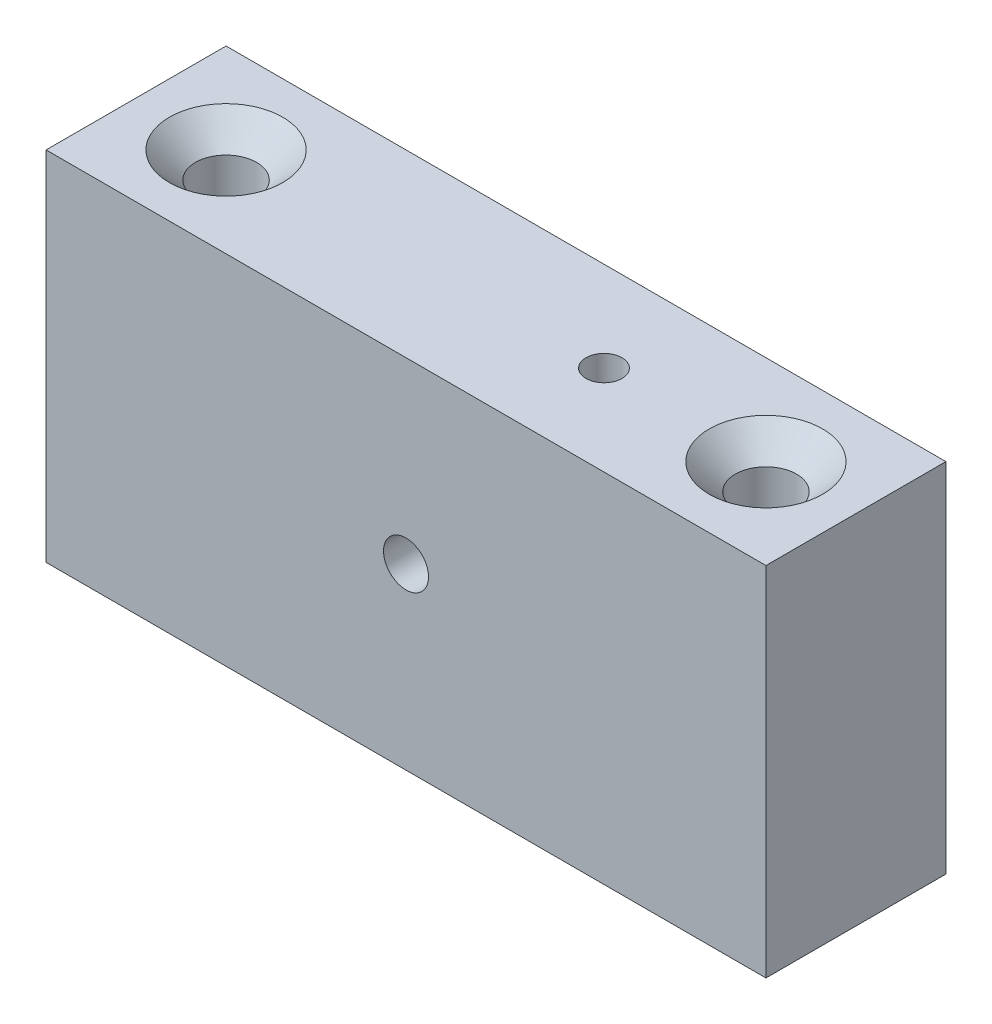
SolidWorks part; units mm, degrees
material "Copper"
ref_plane "Front Plane" through (0, 0, 0) normal (0, 0, 1) x (1, 0, 0)
ref_plane "Top Plane" through (0, 0, 0) normal (0, 1, 0) x (1, 0, 0)
ref_plane "Right Plane" through (0, 0, 0) normal (1, 0, 0) x (0, 0, -1)
sketch "Sketch1" plane through (0, 0, 0) normal (0, 1, 0) x (1, 0, 0)
  line L0 (0, 5) -> (40, 5) construction
  line L1 (0, 0) -> (40, 0)
  line L2 (0, 0) -> (0, 10)
  line L3 (0, 10) -> (40, 10)
  line L4 (40, 0) -> (40, 10)
  line L5 (5, 5) -> (5, 10) construction
  line L6 (35, 10) -> (35, 5) construction
  dimension "D1" = 5
  dimension "D2" = 5
  dimension "D3" = 5
  dimension "D4" = 5
  dimension "D5" = 40
extrude "Boss-Extrude1" add sketch "Sketch1" along normal blind 19.85
sketch "Sketch2" plane through (0, 19.85, 0) normal (0, 1, 0) x (1, 0, 0)
  point P0 (35, 5)
  point P2 (5, 5)
hole_wizard "CSK for M3 Flat Head Machine Screw1" positions "3DSketch1" profile "Sketch3" countersink size "M3" standard "ANSI Metric" end condition through all
sketch3d "3DSketch1"
  point P0 (5, 19.85, -5)
  point P3 (35, 19.85, -5)
sketch "Sketch3" plane through (5, 19.85, -5) normal (1, 0, 0) x (0, 0, 1)
  line L0 (0, 0) -> (0, 19.85)
  line L1 (0, 19.85) -> (1.7, 19.85)
  line L2 (1.7, 19.85) -> (1.7, 1.45)
  line L3 (1.7, 1.45) -> (3.15, 0)
  line L5 (3.15, 0) -> (0, 0)
  line L6 (-1.7, 1.45) -> (-3.15, 0) construction
  line L11 (0, -6.35) -> (0, 107.95) construction
  dimension "Thru Hole Dia." = 3.4
  dimension "Thru Hole Depth" = 19.85
  dimension "Near C'Sink Dia." = 6.3
  dimension "Near C'Sink Angle" = 90
ref_plane "Plane1" through (20, 0, 0) normal (-1, 0, 0) x (0, 0, 1)
sketch "Sketch4" plane through (0, 0, -10) normal (0, 0, -1) x (-1, 0, 0)
  line L0 (-40, 9.925) -> (0, 9.925) construction
  line L1 (-40, 19.85) -> (-40, 0) construction
  line L2 (0, 19.85) -> (0, 0) construction
hole_wizard "M3x0.5 Tapped Hole1" positions "3DSketch2" profile "Sketch5" tap size "M3x0.5" standard "ANSI Metric" end condition through all
sketch3d "3DSketch2"
  line L0 (40, 9.925, -10) -> (0, 9.925, -10) construction
  point P0 (20, 9.925, -10)
  point P4 (20, 9.925, -10)
cosmetic thread "Hole Thread1" parameters "D2"=3
cosmetic thread "Hole Thread2" parameters "D2"=3
sketch "Sketch5" plane through (20, 9.925, -10) normal (1, 0, 0) x (0, 1, 0)
  line L0 (0, 0) -> (0, 10)
  line L1 (0, 10) -> (1.25, 10)
  line L2 (1.25, 10) -> (1.25, 0)
  line L5 (1.25, 0) -> (0, 0)
  line L11 (0, -6.35) -> (0, 107.95) construction
  dimension "Thru Tap Drill Dia." = 2.5
  dimension "Thru Tap Drill Depth" = 10
sketch "Sketch6" plane through (0, 19.85, 0) normal (0, 1, 0) x (1, 0, 0)
  line L0 (40, 5) -> (26, 5) construction
  line L1 (40, 0) -> (40, 10) construction
  dimension "D2" = 14
hole_wizard "Ø2.0mm Dowel Hole1" positions "3DSketch3" profile "Sketch7" hole size "Ø2.0" standard "ANSI Metric" end condition through all
sketch3d "3DSketch3"
  point P0 (26, 19.85, -5)
sketch "Sketch7" plane through (26, 19.85, -5) normal (1, 0, 0) x (0, 0, 1)
  line L0 (0, 0) -> (0, 19.85)
  line L1 (0, 19.85) -> (1, 19.85)
  line L2 (1, 19.85) -> (1, 0)
  line L5 (1, 0) -> (0, 0)
  line L11 (0, -6.35) -> (0, 107.95) construction
  dimension "Thru Hole Dia." = 2
  dimension "Thru Hole Depth" = 19.85
equation "\"D2@Sketch1\"=\"D1@Sketch1\""
equation "\"D3@Sketch1\"=\"D1@Sketch1\""
